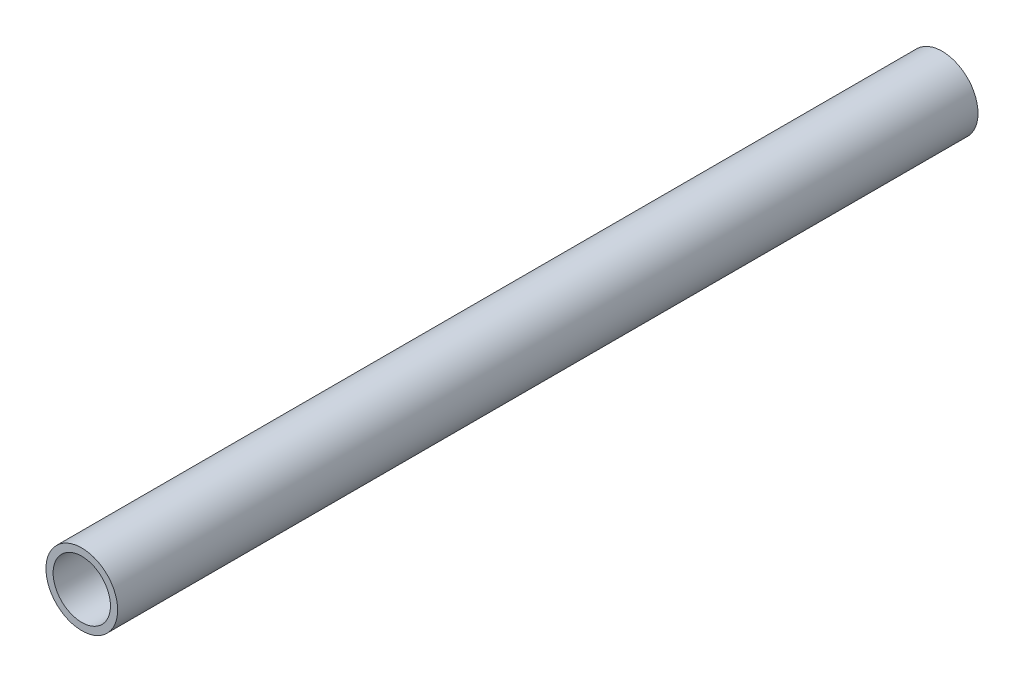
SolidWorks part; units mm, degrees
material "EM-CF"
ref_plane "Płaszczyzna przednia" through (0, 0, 0) normal (0, 0, 1) x (1, 0, 0)
ref_plane "Płaszczyzna górna" through (0, 0, 0) normal (0, 1, 0) x (1, 0, 0)
ref_plane "Płaszczyzna prawa" through (0, 0, 0) normal (1, 0, 0) x (0, 0, -1)
sketch "Szkic1" plane through (0, 0, 0) normal (0, 0, 1) x (1, 0, 0)
  circle A0 centre (0, 0) radius 4
  circle A1 centre (0, 0) radius 5
  dimension "D1" = 1
  dimension "D2" = 10
extrude "Dodanie-wyciągnięcie1" add sketch "Szkic1" along normal blind 120
